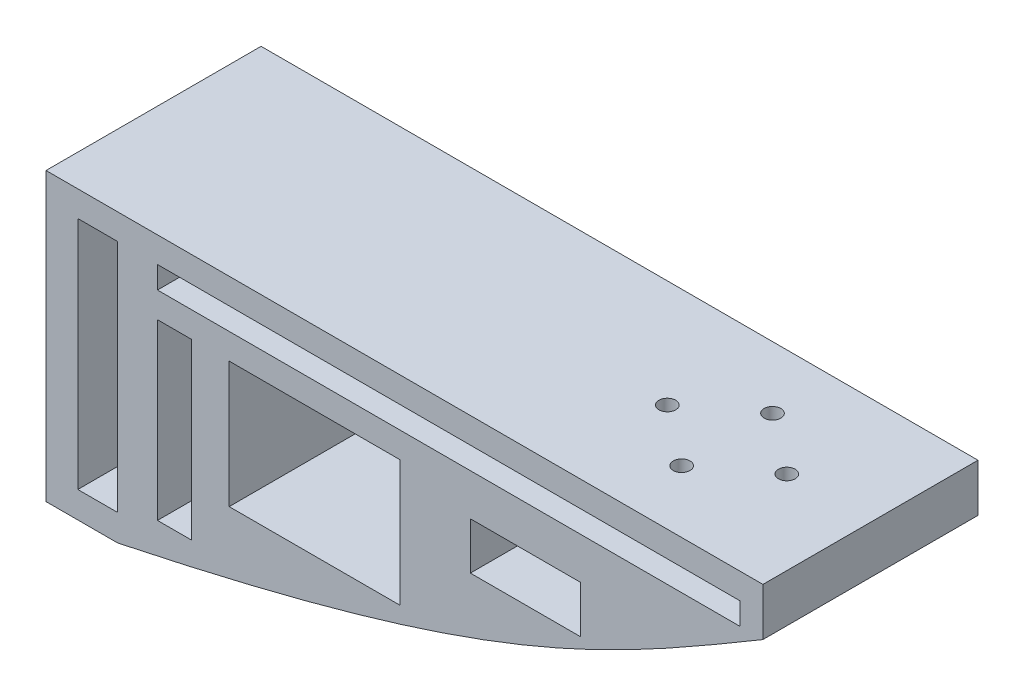
SolidWorks part; units mm, degrees
ref_plane "Front Plane" through (0, 0, 0) normal (0, 0, 1) x (1, 0, 0)
ref_plane "Top Plane" through (0, 0, 0) normal (0, 1, 0) x (1, 0, 0)
ref_plane "Right Plane" through (0, 0, 0) normal (1, 0, 0) x (0, 0, -1)
sketch "Sketch3" plane through (0, 0, 0) normal (0, 0, 1) x (1, 0, 0)
  line L0 (0, -30) -> (0, 30)
  line L1 (0, 30) -> (150, 30)
  line L2 (0, -30) -> (15, -30)
  line L3 (150, 30) -> (150, 20)
  line L5 (6.655, 24.6254) -> (15, 24.6254)
  line L6 (6.655, 24.6254) -> (6.655, -24.4739)
  line L7 (6.655, -24.4739) -> (15, -24.4739)
  line L8 (15, 24.6254) -> (15, -24.4739)
  line L9 (23.3245, 24.6254) -> (145.1635, 24.6254)
  line L10 (23.3245, 24.6254) -> (23.3245, 20)
  line L11 (23.3245, 20) -> (145.1635, 20)
  line L12 (145.1635, 24.6254) -> (145.1635, 20)
  line L13 (23.3245, 14.6237) -> (30.4469, 14.6237)
  line L14 (23.3245, 14.6237) -> (23.3245, -21.7461)
  line L15 (23.3245, -21.7461) -> (30.4469, -21.7461)
  line L16 (30.4469, 14.6237) -> (30.4469, -21.7461)
  line L17 (38.3271, 14.6237) -> (74.0908, 14.6237)
  line L18 (38.3271, 14.6237) -> (38.3271, -11.7444)
  line L19 (38.3271, -11.7444) -> (74.0908, -11.7444)
  line L20 (74.0908, 14.6237) -> (74.0908, -11.7444)
  line L21 (88.7902, 11.2898) -> (111.8245, 11.2898)
  line L22 (88.7902, 11.2898) -> (88.7902, 1.4396)
  line L23 (88.7902, 1.4396) -> (111.8245, 1.4396)
  line L24 (111.8245, 11.2898) -> (111.8245, 1.4396)
  spline S0 degree 3 poles (15, -30) (91.9924, -13.8203) (115.2887, -0.5803) (150, 20) knots 0 0 0 0 1 1 1 1
  point P4 (0, 0)
  dimension "D1" = 60
  dimension "D2" = 150
  dimension "D3" = 15
  dimension "D4" = 10
extrude "Boss-Extrude1" add sketch "Sketch3" along normal mid plane 45
sketch "Sketch4" plane through (0, 0, 0) normal (0, 1, 0) x (1, 0, 0)
  line L18 (107.5, 0) -> (132.5, 0) construction
  line L19 (120, 9.5) -> (120, -9.5) construction
  circle A1 centre (120, 9.5) radius 1.75
  circle A2 centre (132.5, 0) radius 1.75
  circle A3 centre (120, -9.5) radius 1.75
  circle A4 centre (107.5, 0) radius 1.75
  circle A5 centre (107.5, 0) radius 3
  circle A6 centre (120, 9.5) radius 3
  circle A7 centre (132.5, 0) radius 3
  circle A8 centre (120, -9.5) radius 3
  point P0 (0, 0)
  point P3 (0, 0)
  point P4 (0, 0)
  point P5 (77.6563, 37.911)
  point P6 (110.1277, 40.3757)
  point P18 (173.1162, 24.8532)
  point P20 (142.6653, -0.0612)
  point P21 (0, 0)
  point P24 (120, 0)
  dimension "D1" = 3.5
  dimension "D2" = 3.5
  dimension "D3" = 3.5
  dimension "D4" = 3.5
  dimension "D7" = 6
  dimension "D8" = 120
  dimension "D9" = 6
  dimension "D10" = 6
  dimension "D11" = 6
  dimension "D5" = 9.5
  dimension "D6" = 12.5
  dimension "D12" = 25
  dimension "D13" = 19
extrude "Cut-Extrude1" cut sketch "Sketch4" against normal up to surface (32.7997 mm away) from surface contours A4 | A1 | A2 | A3
